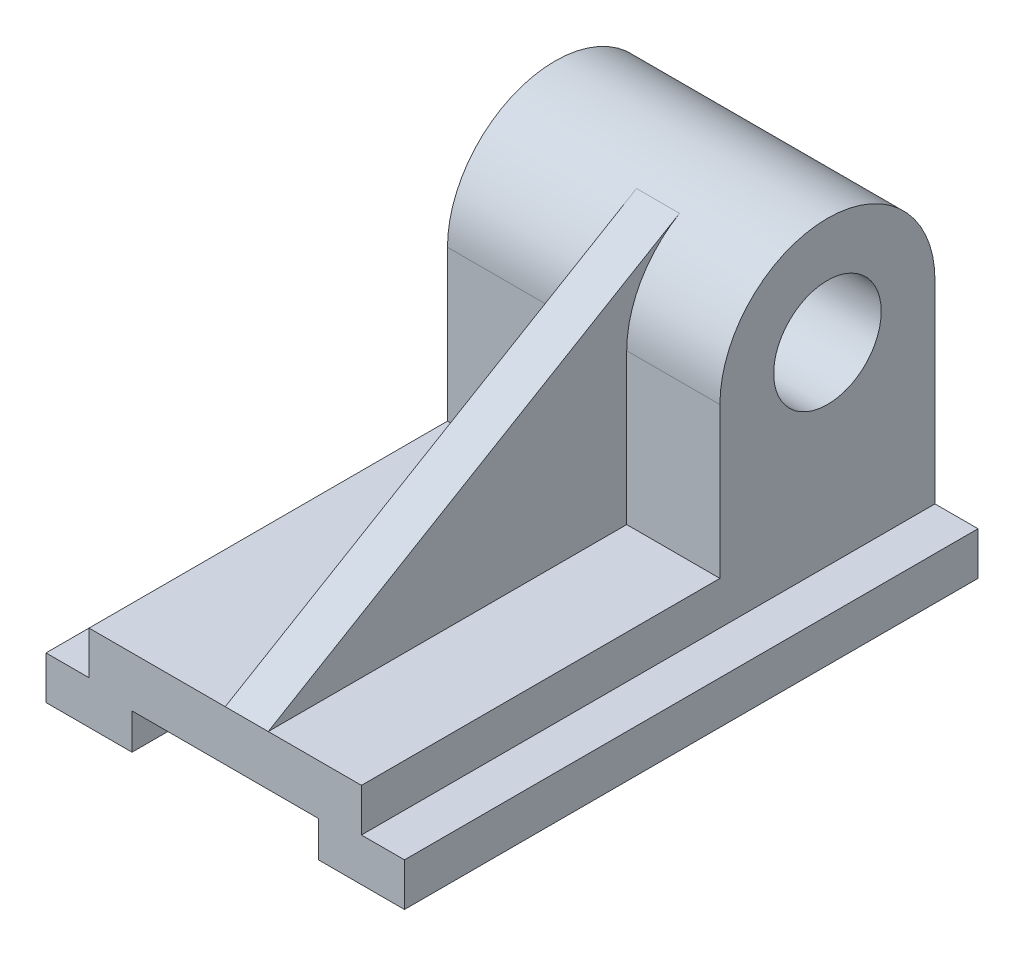
SolidWorks part; units mm, degrees
ref_plane "Front Plane" through (0, 0, 0) normal (0, 0, 1) x (1, 0, 0)
ref_plane "Top Plane" through (0, 0, 0) normal (0, 1, 0) x (1, 0, 0)
ref_plane "Right Plane" through (0, 0, 0) normal (1, 0, 0) x (0, 0, -1)
sketch "Sketch2" plane through (0, 0, 0) normal (0, 0, 1) x (1, 0, 0)
  line L0 (0, 0) -> (0, 12)
  line L1 (0, 12) -> (12, 12)
  line L2 (12, 12) -> (12, 24)
  line L3 (12, 24) -> (88, 24)
  line L4 (88, 24) -> (88, 12)
  line L5 (88, 12) -> (100, 12)
  line L6 (100, 12) -> (100, 0)
  line L7 (100, 0) -> (76, 0)
  line L8 (24, 0) -> (0, 0)
  line L10 (24, 0) -> (24, 10)
  line L11 (24, 10) -> (76, 10)
  line L12 (76, 0) -> (76, 10)
  dimension "D1" = 100
  dimension "D2" = 12
  dimension "D3" = 12
  dimension "D4" = 24
  dimension "D5" = 12
  dimension "D6" = 12
  dimension "D7" = 52
  dimension "D9" = 10
extrude "Boss-Extrude1" add sketch "Sketch2" against normal blind 160
sketch "Sketch3" plane through (88, 0, 0) normal (1, 0, 0) x (0, 0, -1)
  line L0 (100, 24) -> (100, 66)
  line L1 (160, 24) -> (0, 24) construction
  line L2 (160, 66) -> (160, 24)
  line L3 (160, 24) -> (100, 24)
  arc A0 (100, 66) -> (160, 66) centre (130, 66) cw
  circle A1 centre (130, 66) radius 15
  dimension "D2" = 30
  dimension "D3" = 30
  dimension "D1" = 42
extrude "Boss-Extrude3" add sketch "Sketch3" against normal blind 76
ref_plane "Plane1" through (56, 0, 0) normal (1, 0, 0) x (0, 0, -1)
sketch "Sketch5" plane through (56, 0, 0) normal (1, 0, 0) x (0, 0, -1)
  line L0 (0, 24) -> (114.7335, 91.825)
  arc A0 (160, 66) -> (100, 66) centre (130, 66) ccw construction
rib "Rib2" sketch "Sketch5" sketch "Sketch5" thickness 12 extrusion direction parallel to sketch draft on no parameters "D1"=12
